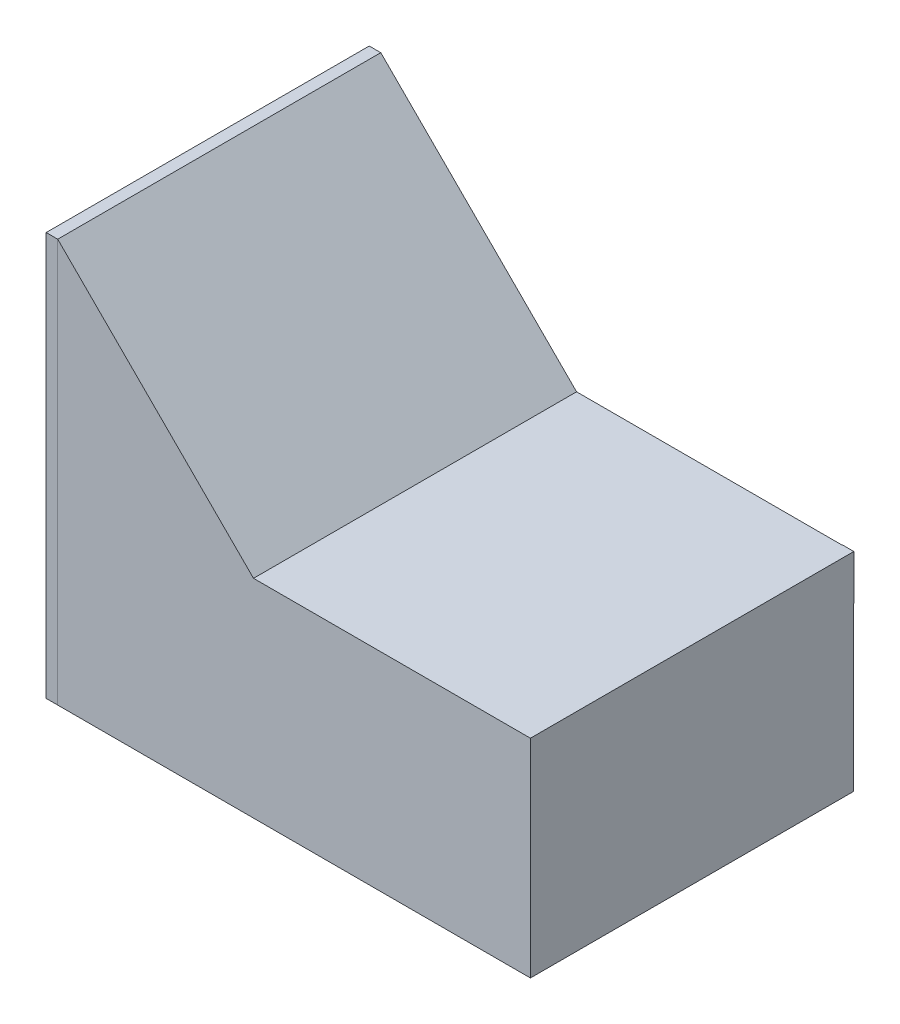
SolidWorks part; units mm, degrees
ref_plane "Front Plane" through (0, 0, 0) normal (0, 0, 1) x (1, 0, 0)
ref_plane "Top Plane" through (0, 0, 0) normal (0, 1, 0) x (1, 0, 0)
ref_plane "Right Plane" through (0, 0, 0) normal (1, 0, 0) x (0, 0, -1)
sketch "Sketch1" plane through (0, 0, 0) normal (0, 0, 1) x (1, 0, 0)
  line L0 (0, 0) -> (-204.8528, 0)
  line L1 (-204.8528, 0) -> (-204.8528, 174.8528)
  line L2 (-204.8528, 174.8528) -> (-120, 90)
  line L3 (-120, 90) -> (0, 90)
  line L4 (0, 90) -> (0, 0)
  dimension "D1" = 120
  dimension "D2" = 90
  dimension "D3" = 135
  dimension "D4" = 120
extrude "Boss-Extrude1" add sketch "Sketch1" against normal blind 5
ref_plane "Plane1" through (0, 90, 0) normal (0, 1, 0) x (1, 0, 0)
sketch "Sketch2" plane through (0, 90, 0) normal (0, 1, 0) x (1, 0, 0)
  line L0 (-120, 0) -> (-120, 140)
  line L1 (-120, 140) -> (0, 140)
  line L2 (0, 140) -> (0, 0)
  line L3 (0, 0) -> (-120, 0)
  dimension "D1" = 140
extrude "Boss-Extrude2" add sketch "Sketch2" against normal blind 5
ref_plane "Plane2" through (-15, -15, 0) normal (0.7071, 0.7071, 0) x (0, 0, -1)
sketch "Sketch4" plane through (-15, -15, 0) normal (0.7071, 0.7071, 0) x (0, 0, -1)
  line L0 (0, 268.4924) -> (140, 268.4924)
  line L1 (140, 268.4924) -> (140, 148.4924)
  line L2 (140, 148.4924) -> (5, 148.4924) construction
  line L3 (140, 148.4924) -> (5, 148.4924)
  line L4 (5, 148.4924) -> (5, 268.4924)
  dimension "D1" = 140
extrude "Boss-Extrude6" add sketch "Sketch4" against normal blind 5 separate body contours L4 L3 L1 L0
ref_plane "Plane3" through (-204.8528, 0, 0) normal (-1, 0, 0) x (0, 0, 1)
sketch "Sketch5" plane through (-204.8528, 0, 0) normal (-1, 0, 0) x (0, 0, 1)
  line L0 (0, 174.8528) -> (-140, 174.8528)
  line L1 (-140, 174.8528) -> (-140, 0)
  line L2 (-140, 0) -> (0, 0)
  line L3 (0, 174.8528) -> (0, 0)
extrude "Boss-Extrude8" add sketch "Sketch5" along normal blind 5 separate body
sketch "Sketch6" plane through (-120, 0, 0) normal (-1, 0, 0) x (0, 0, 1)
  line L4 (-140, 85) -> (-5, 85)
  line L5 (-5, 85) -> (-5, 90)
  line L6 (-5, 90) -> (-140, 90)
  line L7 (-140, 90) -> (-140, 85)
  line L8 (-140, 85) -> (-5, 85)
  line L9 (-5, 85) -> (-5, 90)
  line L10 (-5, 90) -> (-140, 90)
  line L11 (-140, 90) -> (-140, 85)
  dimension "D1" = 0
extrude "Boss-Extrude9" add sketch "Sketch6" along normal blind 5
ref_plane "Plane4" through (0, 0, 0) normal (1, 0, 0) x (0, 0, -1)
sketch "Sketch7" plane through (0, 0, 0) normal (1, 0, 0) x (0, 0, -1)
  line L0 (0, 90) -> (140.1486, 90)
  line L1 (66, 90) -> (-66, 90) construction
  line L2 (0, 0) -> (0, 90) construction
  line L3 (140.1486, 90) -> (140, 0)
  line L4 (140, 0) -> (0, 0)
  line L5 (0, 0) -> (0, 90)
extrude "Boss-Extrude10" add sketch "Sketch7" against normal blind 5
ref_plane "Plane6" through (0, 0, -70) normal (0, 0, 1) x (1, 0, 0)
mirror "Mirror1" about plane through (0, 0, -70) normal (0, 0, 1) of "Boss-Extrude1"
